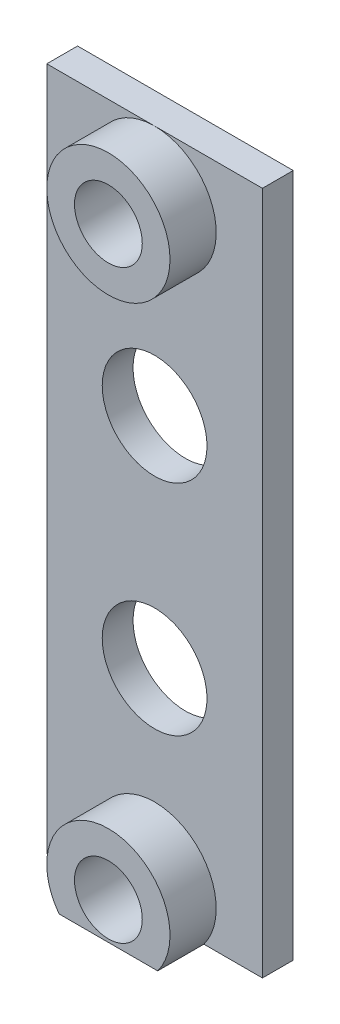
SolidWorks part; units mm, degrees
material "PVC Rigid"
ref_plane "Front Plane" through (0, 0, 0) normal (0, 0, 1) x (1, 0, 0)
ref_plane "Top Plane" through (0, 0, 0) normal (0, 1, 0) x (1, 0, 0)
ref_plane "Right Plane" through (0, 0, 0) normal (1, 0, 0) x (0, 0, -1)
sketch "Sketch1" plane through (0, 0, 0) normal (0, 0, 1) x (1, 0, 0)
  line L1 (-35.5187, -49.5) -> (-28.5187, -49.5)
  line L2 (-35.5187, -49.5) -> (-35.5187, -26.5)
  line L3 (-35.5187, -26.5) -> (-28.5187, -26.5)
  line L4 (-28.5187, -49.5) -> (-28.5187, -26.5)
extrude "Retainer_plate" add sketch "Sketch1" along normal blind 1 from offset 34.5
sketch "Sketch2" plane through (0, 0, 0) normal (0, 0, 1) x (1, 0, 0)
  circle A0 centre (-32.0187, -47.5) radius 2
  circle A1 centre (-32.0187, -28.5) radius 2
extrude "Retainer_mounting_spacers" add sketch "Sketch2" along normal blind 1.5 from offset 35.5
sketch "Sketch3" plane through (0, 0, 0) normal (0, 0, 1) x (1, 0, 0)
  circle A0 centre (-32.0187, -41.7454) radius 1.7
  circle A1 centre (-32.0187, -34.6434) radius 1.7
  circle A2 centre (-32.0187, -47.5) radius 1.1
  circle A3 centre (-32.0187, -28.5) radius 1.1
extrude "Retainer_clearance_holes" cut sketch "Sketch3" along normal blind 4 from offset 34
sketch "Sketch4" plane through (0, 0, 0) normal (0, 0, 1) x (1, 0, 0)
  line L0 (-40, -55) -> (-25, -55)
  line L1 (-25, -55) -> (-25, -48.7)
  line L2 (-25, -48.7) -> (-40, -48.7)
  line L3 (-40, -48.7) -> (-40, -55)
extrude "Clear_end_wall" cut sketch "Sketch4" along normal blind 6 from offset 33
